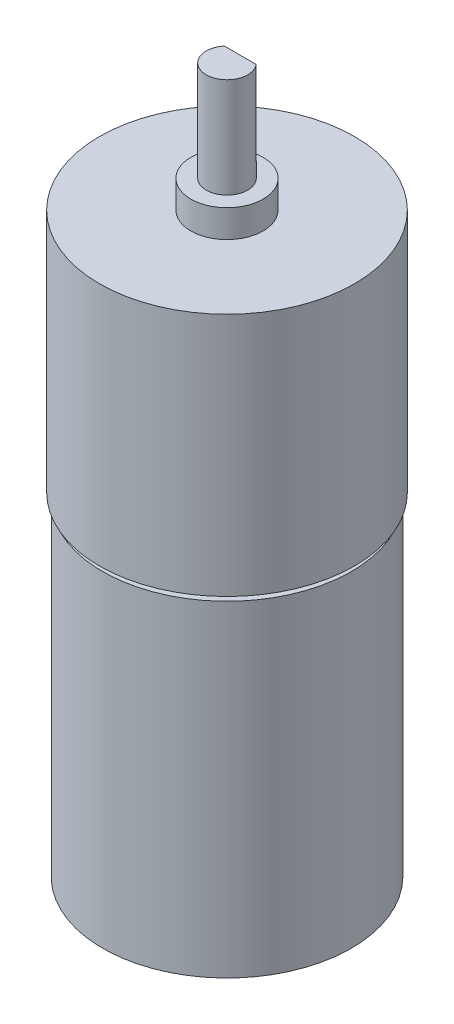
SolidWorks part; units mm, degrees
ref_plane "前视基准面" through (0, 0, 0) normal (0, 0, 1) x (1, 0, 0)
ref_plane "上视基准面" through (0, 0, 0) normal (0, 1, 0) x (1, 0, 0)
ref_plane "右视基准面" through (0, 0, 0) normal (1, 0, 0) x (0, 0, -1)
other "Configuration Table"
sketch "草图1" plane through (0, 0, 0) normal (0, 1, 0) x (1, 0, 0)
  circle A0 centre (0, 0) radius 12
  dimension "D1" = 24
extrude "凸台-拉伸1" add sketch "草图1" along normal blind 54.3
sketch "草图2" plane through (0, 54.3, 0) normal (0, 1, 0) x (1, 0, 0)
  circle A0 centre (0, 0) radius 3.4
  circle A1 centre (0, 0) radius 1.95
  dimension "D1" = 6.8
  dimension "D2" = 3.9
extrude "凸台-拉伸2" add sketch "草图2" along normal blind 2.6
sketch "草图3" plane through (0, 54.3, 0) normal (0, 1, 0) x (1, 0, 0)
  circle A0 centre (0, 0) radius 1.95
extrude "凸台-拉伸3" add sketch "草图3" along normal blind 12
sketch "草图4" plane through (0, 66.3, 0) normal (0, 1, 0) x (1, 0, 0)
  line L0 (-1.5, 1.246) -> (1.5, 1.246)
  circle A0 centre (0, 0) radius 1.95 construction
  arc A1 (-1.5, 1.246) -> (1.5, 1.246) centre (0, 0) cw
  dimension "D1" = 3
extrude "切除-拉伸1" cut sketch "草图4" against normal blind 8
ref_axis "基准轴1" through (0, -3.315, 0) along (0, 1, 0)
sketch "草图5" plane through (0, 0, 0) normal (1, 0, 0) x (0, 0, -1)
  line L0 (12, 0) -> (12, 54.3) construction
  line L1 (12, 31.3) -> (11, 31.3)
  line L2 (12, 31.3) -> (12, 30.7)
  line L3 (11.7, 30.7) -> (11, 30.7)
  line L4 (11, 31.3) -> (11, 30.7)
  line L5 (12, 54.3) -> (-12, 54.3) construction
  line L6 (11.7, 30.7) -> (11.7, 0)
  line L7 (11.7, 0) -> (12, 0)
  line L8 (12, 30.7) -> (12, 0)
  point P10 (8.6865, 1.2695)
  dimension "D1" = 0.6
  dimension "D2" = 23
  dimension "D3" = 1
  dimension "D4" = 0.3
revolve "切除-旋转1" cut sketch "草图5" angle 360 about axis through (0, -3.315, 0) along (0, 1, 0)
